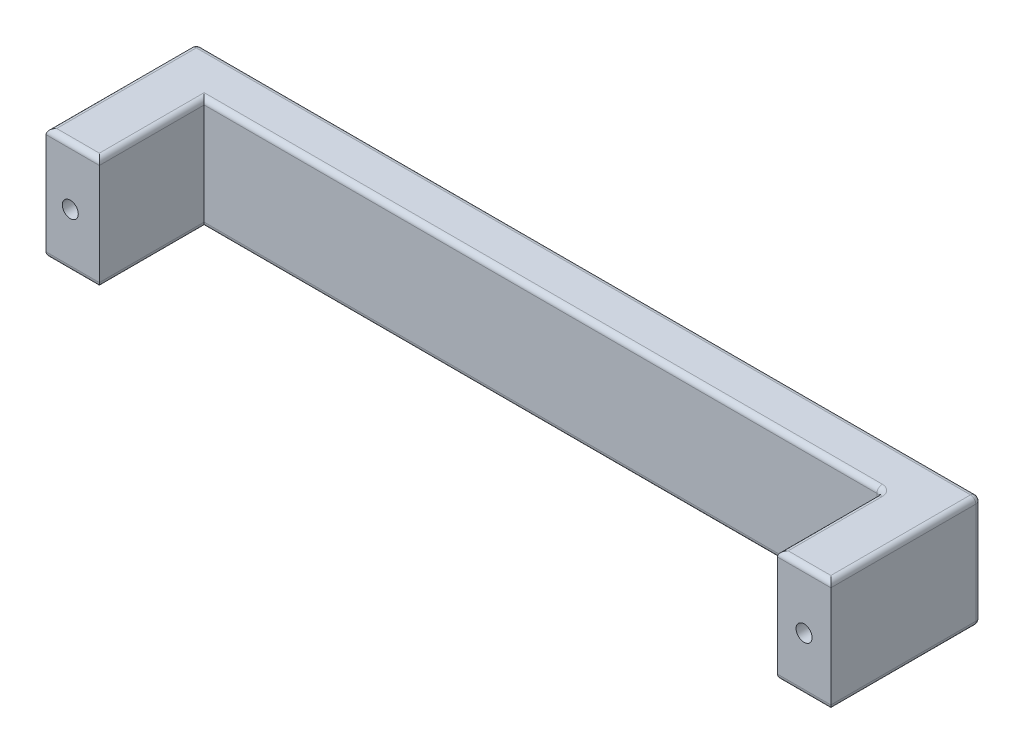
SolidWorks part; units mm, degrees
ref_plane "Alzado" through (0, 0, 0) normal (0, 0, 1) x (1, 0, 0)
ref_plane "Planta" through (0, 0, 0) normal (0, 1, 0) x (1, 0, 0)
ref_plane "Vista lateral" through (0, 0, 0) normal (1, 0, 0) x (0, 0, -1)
sketch "Croquis1" plane through (0, 0, 0) normal (0, 1, 0) x (1, 0, 0)
  line L0 (-45.5556, 0) -> (-45.5556, 28.1481)
  line L1 (-45.5556, 28.1481) -> (101.4815, 28.1481)
  line L2 (101.4815, 28.1481) -> (101.4815, 0)
  line L3 (101.4815, 0) -> (91.4815, 0)
  line L4 (91.4815, 0) -> (91.4815, 19.6296)
  line L5 (91.4815, 19.6296) -> (-35.5556, 19.6296)
  line L6 (-35.5556, 19.6296) -> (-35.5556, 0)
  line L7 (-35.5556, 0) -> (-45.5556, 0)
  dimension "D1" = 10
  dimension "D2" = 10
extrude "Saliente-Extruir1" add sketch "Croquis1" along normal blind 21
fillet "Redondeo1" radius 1 19 edges at (91.4815, 21, -9.8148) (96.4815, 21, 0) (101.4815, 21, -14.0741) (27.963, 21, -28.1481) (-45.5556, 21, -14.0741) (-40.5556, 21, 0) (27.963, 21, -19.6296) (27.963, 0, -28.1481) (101.4815, 10.5, -28.1481) (-45.5556, 0, -14.0741) (-45.5556, 10.5, -28.1481) (91.4815, 10.5, -19.6296) (91.4815, 0, -9.8148) (96.4815, 0, 0) (101.4815, 0, -14.0741) (27.963, 0, -19.6296) (-40.5556, 0, 0) (-35.5556, 0, -9.8148) (-35.5556, 21, -9.8148)
hole_wizard "Ranuras de espiga de Ø3.0mm1" positions "Croquis2" profile "Croquis3" hole size "Ø3.0" standard "ISO"
sketch "Croquis2" plane through (0, 0, 0) normal (0, 0, 1) x (1, 0, 0)
  point P0 (-41.0074, 10.1449)
  point P2 (96.4627, 10.1449)
sketch "Croquis3" plane through (-41.0074, 10.1449, 0) normal (1, 0, 0) x (0, -1, 0)
  line L0 (0, 0) -> (0, 15.9013)
  line L1 (0, 15.9013) -> (1.5, 15)
  line L2 (1.5, 15) -> (1.5, 0)
  line L5 (1.5, 0) -> (0, 0)
  line L10 (0, 15.9013) -> (-1.5, 15) construction
  line L11 (0, -6.35) -> (0, 107.95) construction
  dimension "Diámetro de taladro" = 3
  dimension "Profundidad de taladro" = 15
  dimension "Ángulo de perforador" = 118
